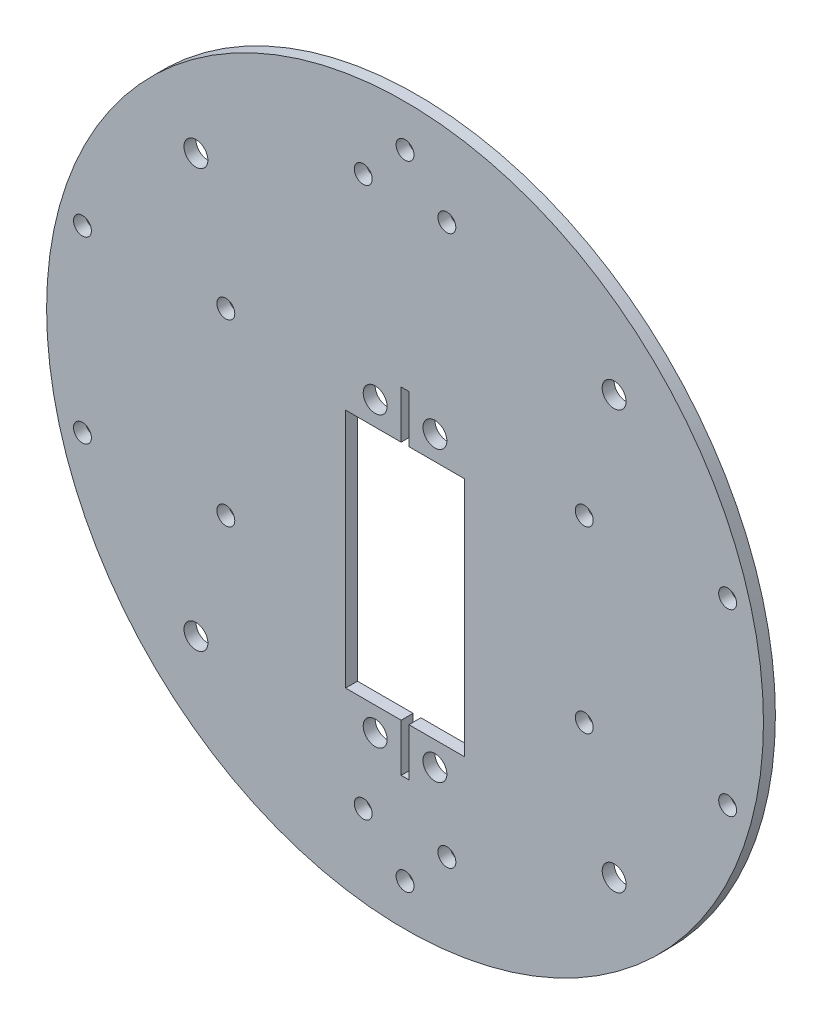
SolidWorks part; units mm, degrees
material "普通碳钢"
ref_plane "前视" through (0, 0, 0) normal (0, 0, 1) x (1, 0, 0)
ref_plane "上视" through (0, 0, 0) normal (0, 1, 0) x (1, 0, 0)
ref_plane "右视" through (0, 0, 0) normal (1, 0, 0) x (0, 0, -1)
sketch "草图2" plane through (0, 0, 0) normal (0, 0, 1) x (1, 0, 0)
  line L0 (1.0372, -12.2442) -> (1.0372, -20.2442)
  line L1 (2.3372, -20.2442) -> (2.3372, -12.2442)
  line L2 (2.3372, -12.2442) -> (11.6467, -12.2442)
  line L3 (11.6467, -12.2442) -> (11.6467, 28.0558)
  line L4 (11.6467, 28.0558) -> (2.3372, 28.0558)
  line L5 (2.3372, 28.0558) -> (2.3372, 36.0558)
  line L6 (1.0372, 36.0558) -> (1.0372, 28.0558)
  line L7 (1.0372, 28.0558) -> (-8.2722, 28.0558)
  line L8 (-8.2722, 28.0558) -> (-8.2722, -12.2442)
  line L9 (-8.2722, -12.2442) -> (1.0372, -12.2442)
  line L10 (14.1872, 13.7581) -> (14.1872, 7.7581)
  line L11 (17.1872, 7.7581) -> (17.1872, 13.7581)
  line L12 (-10.8128, 7.7581) -> (-10.8128, 13.7581)
  line L13 (-13.8128, 13.7581) -> (-13.8128, 7.7581)
  line L14 (-10.8128, 21.7581) -> (-10.8128, 27.7581)
  line L15 (-13.8128, 27.7581) -> (-13.8128, 21.7581)
  line L16 (17.1872, 21.7581) -> (17.1872, 27.7581)
  line L17 (14.1872, 27.7581) -> (14.1872, 21.7581)
  line L18 (15.6872, -29.7419) -> (22.6872, -29.7419)
  line L19 (22.6872, -26.7419) -> (15.6872, -26.7419)
  line L20 (-19.3128, -29.7419) -> (-12.3128, -29.7419)
  line L21 (-12.3128, -26.7419) -> (-19.3128, -26.7419)
  line L22 (-19.3128, 62.2581) -> (-12.3128, 62.2581)
  line L23 (-12.3128, 65.2581) -> (-19.3128, 65.2581)
  line L24 (15.6872, 62.2581) -> (22.6872, 62.2581)
  line L25 (22.6872, 65.2581) -> (15.6872, 65.2581)
  line L26 (-19.3128, 37.2581) -> (-12.3128, 37.2581)
  line L27 (-12.3128, 40.2581) -> (-19.3128, 40.2581)
  line L28 (15.6872, 37.2581) -> (22.6872, 37.2581)
  line L29 (22.6872, 40.2581) -> (15.6872, 40.2581)
  line L30 (49.6872, 16.2581) -> (55.6872, 16.2581)
  line L31 (55.6872, 19.2581) -> (49.6872, 19.2581)
  line L32 (-52.3128, 16.2581) -> (-46.3128, 16.2581)
  line L33 (-46.3128, 19.2581) -> (-52.3128, 19.2581)
  line L34 (-5.3128, 62.2581) -> (8.6872, 62.2581)
  line L35 (8.6872, 65.2581) -> (-5.3128, 65.2581)
  line L36 (1.0372, 36.0558) -> (2.3372, 36.0558)
  line L37 (2.3372, -20.2442) -> (1.0372, -20.2442)
  circle A0 centre (1.6855, 17.7599) radius 60
  circle A1 centre (-3.3128, 32.0508) radius 2
  circle A2 centre (6.6872, -16.2492) radius 2
  circle A3 centre (-3.3128, -16.2492) radius 2
  circle A4 centre (-28.3128, 32.7581) radius 1.5
  circle A5 centre (-52.3128, 32.7581) radius 1.5
  circle A6 centre (-28.3128, 2.7581) radius 1.5
  circle A7 centre (-52.3128, 2.7581) radius 1.5
  circle A8 centre (31.6872, 32.7581) radius 1.5
  circle A9 centre (55.6872, 32.7581) radius 1.5
  circle A10 centre (31.6872, 2.7581) radius 1.5
  circle A11 centre (55.6872, 2.7581) radius 1.5
  circle A12 centre (36.689, -17.2365) radius 2
  circle A13 centre (-33.311, -17.2436) radius 2
  circle A14 centre (-33.3181, 52.7564) radius 2
  circle A15 centre (36.6819, 52.7635) radius 2
  circle A16 centre (-12.3128, -3.2419) radius 1.5
  circle A17 centre (15.6872, -3.2419) radius 1.5
  circle A18 centre (42.6872, 24.7581) radius 1.5
  circle A19 centre (42.6872, 10.7581) radius 1.5
  circle A20 centre (35.6872, 17.7581) radius 1.5
  circle A21 centre (-39.3128, 24.7581) radius 1.5
  circle A22 centre (-39.3128, 10.7581) radius 1.5
  circle A23 centre (-32.3128, 17.7581) radius 1.5
  circle A24 centre (1.6872, -35.2419) radius 1.5
  circle A25 centre (6.6872, 32.0508) radius 2
  circle A26 centre (1.6872, -28.2419) radius 3
  circle A27 centre (8.6872, -28.2419) radius 1.5
  circle A28 centre (-5.3128, -28.2419) radius 1.5
  circle A29 centre (49.6872, 10.7581) radius 1.5
  circle A30 centre (42.6872, 17.7581) radius 1.5
  circle A31 centre (49.6872, 24.7581) radius 1.5
  circle A32 centre (-39.3128, 17.7581) radius 1.5
  circle A33 centre (-46.3128, 10.7581) radius 1.5
  circle A34 centre (-46.3128, 24.7581) radius 1.5
  circle A35 centre (1.6872, 70.7581) radius 1.5
  circle A36 centre (1.6872, 56.7581) radius 1.5
  arc A37 (14.1872, 7.7581) -> (17.1872, 7.7581) centre (15.6872, 7.7581) ccw
  arc A38 (17.1872, 13.7581) -> (14.1872, 13.7581) centre (15.6872, 13.7581) ccw
  arc A39 (-13.8128, 7.7581) -> (-10.8128, 7.7581) centre (-12.3128, 7.7581) ccw
  arc A40 (-10.8128, 13.7581) -> (-13.8128, 13.7581) centre (-12.3128, 13.7581) ccw
  arc A41 (-13.8128, 21.7581) -> (-10.8128, 21.7581) centre (-12.3128, 21.7581) ccw
  arc A42 (-10.8128, 27.7581) -> (-13.8128, 27.7581) centre (-12.3128, 27.7581) ccw
  arc A43 (17.1872, 27.7581) -> (14.1872, 27.7581) centre (15.6872, 27.7581) ccw
  arc A44 (14.1872, 21.7581) -> (17.1872, 21.7581) centre (15.6872, 21.7581) ccw
  arc A45 (22.6872, -29.7419) -> (22.6872, -26.7419) centre (22.6872, -28.2419) ccw
  arc A46 (15.6872, -26.7419) -> (15.6872, -29.7419) centre (15.6872, -28.2419) ccw
  arc A47 (-12.3128, -29.7419) -> (-12.3128, -26.7419) centre (-12.3128, -28.2419) ccw
  arc A48 (-19.3128, -26.7419) -> (-19.3128, -29.7419) centre (-19.3128, -28.2419) ccw
  arc A49 (-12.3128, 62.2581) -> (-12.3128, 65.2581) centre (-12.3128, 63.7581) ccw
  arc A50 (-19.3128, 65.2581) -> (-19.3128, 62.2581) centre (-19.3128, 63.7581) ccw
  arc A51 (22.6872, 62.2581) -> (22.6872, 65.2581) centre (22.6872, 63.7581) ccw
  arc A52 (15.6872, 65.2581) -> (15.6872, 62.2581) centre (15.6872, 63.7581) ccw
  arc A53 (-19.3128, 40.2581) -> (-19.3128, 37.2581) centre (-19.3128, 38.7581) ccw
  arc A54 (-12.3128, 37.2581) -> (-12.3128, 40.2581) centre (-12.3128, 38.7581) ccw
  arc A55 (22.6872, 37.2581) -> (22.6872, 40.2581) centre (22.6872, 38.7581) ccw
  arc A56 (15.6872, 40.2581) -> (15.6872, 37.2581) centre (15.6872, 38.7581) ccw
  arc A57 (55.6872, 16.2581) -> (55.6872, 19.2581) centre (55.6872, 17.7581) ccw
  arc A58 (49.6872, 19.2581) -> (49.6872, 16.2581) centre (49.6872, 17.7581) ccw
  arc A59 (-52.3128, 19.2581) -> (-52.3128, 16.2581) centre (-52.3128, 17.7581) ccw
  arc A60 (-46.3128, 16.2581) -> (-46.3128, 19.2581) centre (-46.3128, 17.7581) ccw
  arc A61 (-5.3128, 65.2581) -> (-5.3128, 62.2581) centre (-5.3128, 63.7581) ccw
  arc A62 (8.6872, 62.2581) -> (8.6872, 65.2581) centre (8.6872, 63.7581) ccw
  circle A63 centre (1.6855, 17.7599) radius 49.4975 construction
  point P1 (0, 0)
  dimension "D1" = 3
  dimension "D5" = 70
  dimension "D2" = 70
  dimension "D3" = 70
  dimension "D4" = 70
extrude "凸台-拉伸1" add sketch "草图2" along normal blind 2
sketch "草图3" plane through (0, 0, 2) normal (0, 0, 1) x (1, 0, 0)
  line L1 (21.2985, -8.1421) -> (13.1361, -8.1421)
  line L2 (21.2985, -8.1421) -> (21.2985, 32.3432)
  line L3 (21.2985, 32.3432) -> (13.1361, 32.3432)
  line L4 (13.1361, -8.1421) -> (13.1361, 32.3432)
  line L5 (57.905, 7.0332) -> (30.7652, 7.0332)
  line L6 (57.905, 7.0332) -> (57.905, 28.0558)
  line L7 (57.905, 28.0558) -> (30.7652, 28.0558)
  line L8 (30.7652, 7.0332) -> (30.7652, 28.0558)
  line L9 (26.2311, 36.5257) -> (11.6467, 36.5257)
  line L10 (26.2311, 36.5257) -> (26.2311, 42.576)
  line L11 (26.2311, 42.576) -> (11.6467, 42.576)
  line L12 (11.6467, 36.5257) -> (11.6467, 42.576)
  line L13 (26.2311, 53.7593) -> (-22.6247, 53.7593)
  line L14 (26.2311, 53.7593) -> (26.2311, 66.6516)
  line L15 (26.2311, 66.6516) -> (-22.6247, 66.6516)
  line L16 (-22.6247, 53.7593) -> (-22.6247, 66.6516)
  line L17 (-4.927, 73.215) -> (7.9653, 73.215)
  line L18 (-4.927, 73.215) -> (-4.927, 68.6441)
  line L19 (-4.927, 68.6441) -> (7.9653, 68.6441)
  line L20 (7.9653, 73.215) -> (7.9653, 68.6441)
  line L21 (-9.5656, -6.7447) -> (-18.444, -6.7447)
  line L22 (-9.5656, -6.7447) -> (-9.5656, 32.3432)
  line L23 (-9.5656, 32.3432) -> (-18.444, 32.3432)
  line L24 (-18.444, -6.7447) -> (-18.444, 32.3432)
  line L25 (-7.0509, 35.2928) -> (-26.8491, 35.2928)
  line L26 (-7.0509, 35.2928) -> (-7.0509, 45.6025)
  line L27 (-7.0509, 45.6025) -> (-26.8491, 45.6025)
  line L28 (-26.8491, 35.2928) -> (-26.8491, 45.6025)
  line L29 (-28.6947, 7.9058) -> (-55.3608, 7.9058)
  line L30 (-28.6947, 7.9058) -> (-28.6947, 27.7581)
  line L31 (-28.6947, 27.7581) -> (-55.3608, 27.7581)
  line L32 (-55.3608, 7.9058) -> (-55.3608, 27.7581)
  line L33 (-9.5656, -31.938) -> (-23.352, -31.938)
  line L34 (-9.5656, -31.938) -> (-9.5656, -24.1979)
  line L35 (-9.5656, -24.1979) -> (-23.352, -24.1979)
  line L36 (-23.352, -31.938) -> (-23.352, -24.1979)
  line L37 (26.2311, -31.0898) -> (11.6467, -31.0898)
  line L38 (26.2311, -31.0898) -> (26.2311, -24.1979)
  line L39 (26.2311, -24.1979) -> (11.6467, -24.1979)
  line L40 (11.6467, -31.0898) -> (11.6467, -24.1979)
  line L41 (5.6737, -31.938) -> (-2.2508, -31.938)
  line L42 (5.6737, -31.938) -> (5.6737, -24.1979)
  line L43 (5.6737, -24.1979) -> (-2.2508, -24.1979)
  line L44 (-2.2508, -31.938) -> (-2.2508, -24.1979)
extrude "凸台-拉伸2" add sketch "草图3" against normal blind 2
sketch "草图4" plane through (0, 0, 2) normal (0, 0, 1) x (1, 0, 0)
  line L1 (1.6855, 17.7599) -> (-58.3145, 17.7599) construction
  circle A1 centre (1.6872, -35.2419) radius 1.5
  circle A2 centre (-5.3128, -28.2419) radius 1.5
  circle A3 centre (8.6872, -28.2419) radius 1.5
  circle A4 centre (8.6872, 63.7617) radius 1.5
  circle A5 centre (-5.3128, 63.7617) radius 1.5
  circle A6 centre (1.6872, 70.7617) radius 1.5
extrude "切除-拉伸1" cut sketch "草图4" against normal blind 2
